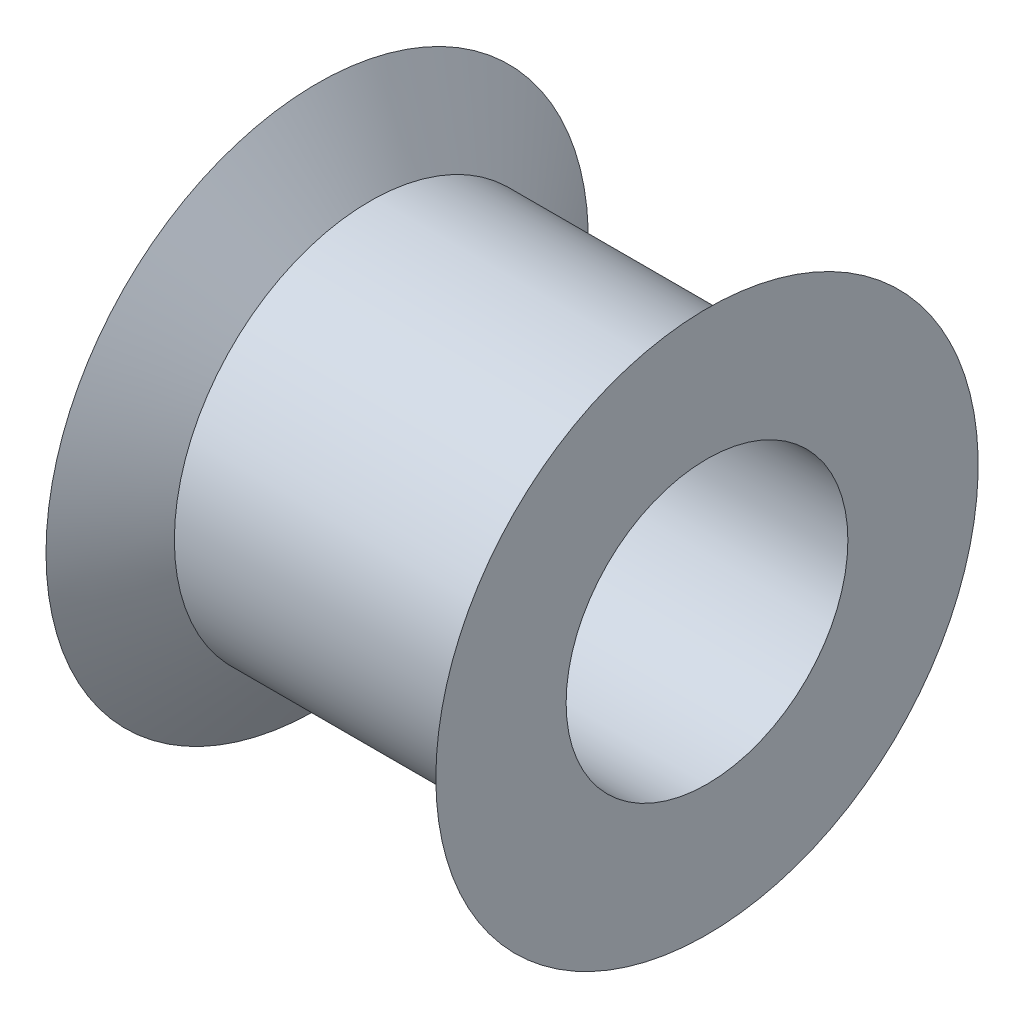
SolidWorks part; units mm, degrees
ref_plane "Front Plane" through (0, 0, 0) normal (0, 0, 1) x (1, 0, 0)
ref_plane "Top Plane" through (0, 0, 0) normal (0, 1, 0) x (1, 0, 0)
ref_plane "Right Plane" through (0, 0, 0) normal (1, 0, 0) x (0, 0, -1)
sketch "Sketch2" plane through (0, 0, 0) normal (0, 0, 1) x (1, 0, 0)
  line L0 (0, 2.286) -> (6.3256, 2.286)
  line L1 (6.3256, 2.286) -> (6.3256, 4.4)
  line L2 (0, 0) -> (14.6931, 0) construction
  line L3 (0, 2.286) -> (0, 4.4)
  line L4 (0.8578, 3.175) -> (5.4678, 3.175)
  line L5 (0, 4.4) -> (0.8578, 3.175)
  line L6 (5.4678, 3.175) -> (6.3256, 4.4)
  line L7 (6.3256, 6.0454) -> (6.3256, -1.6664) construction
  point P9 (3.1628, 3.175)
  point P10 (3.1628, 2.286)
  dimension "D1" = 4.572
  dimension "D2" = 6.35
  dimension "D3" = 35
revolve "Revolve1" add sketch "Sketch2" angle 360 about L2
